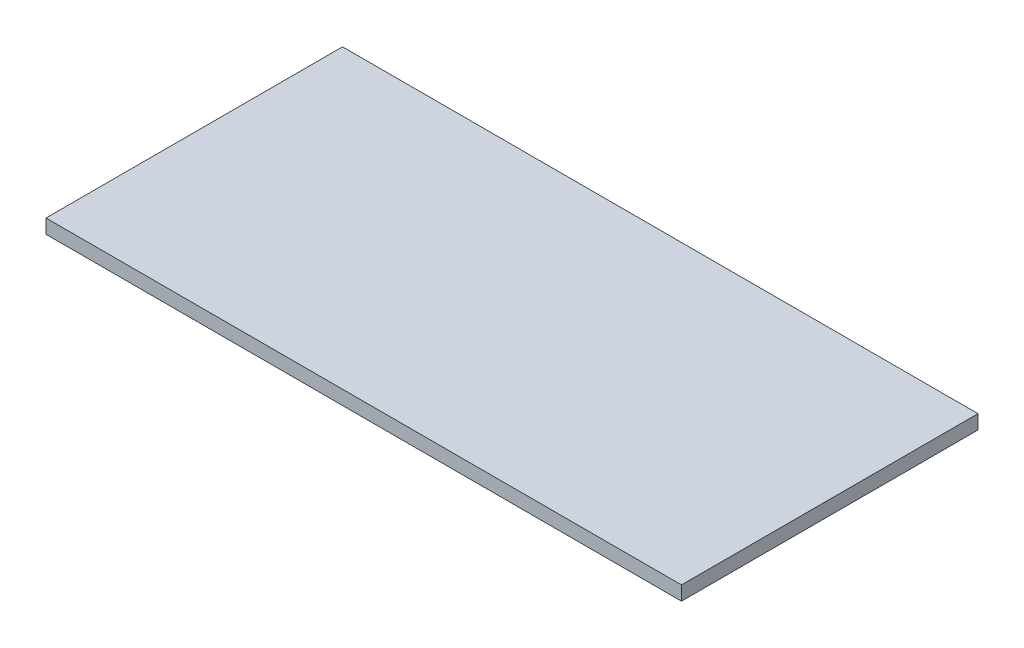
SolidWorks part; units mm, degrees
ref_plane "前视基准面" through (0, 0, 0) normal (0, 0, 1) x (1, 0, 0)
ref_plane "上视基准面" through (0, 0, 0) normal (0, 1, 0) x (1, 0, 0)
ref_plane "右视基准面" through (0, 0, 0) normal (1, 0, 0) x (0, 0, -1)
sketch "草图1" plane through (0, 0, 0) normal (0, 1, 0) x (1, 0, 0)
  line L1 (-47.1815, 24.0646) -> (42.8185, 24.0646)
  line L2 (-47.1815, 24.0646) -> (-47.1815, -17.9354)
  line L3 (-47.1815, -17.9354) -> (42.8185, -17.9354)
  line L4 (42.8185, 24.0646) -> (42.8185, -17.9354)
  dimension "D1" = 42
  dimension "D2" = 90
extrude "凸台-拉伸1" add sketch "草图1" along normal blind 2
